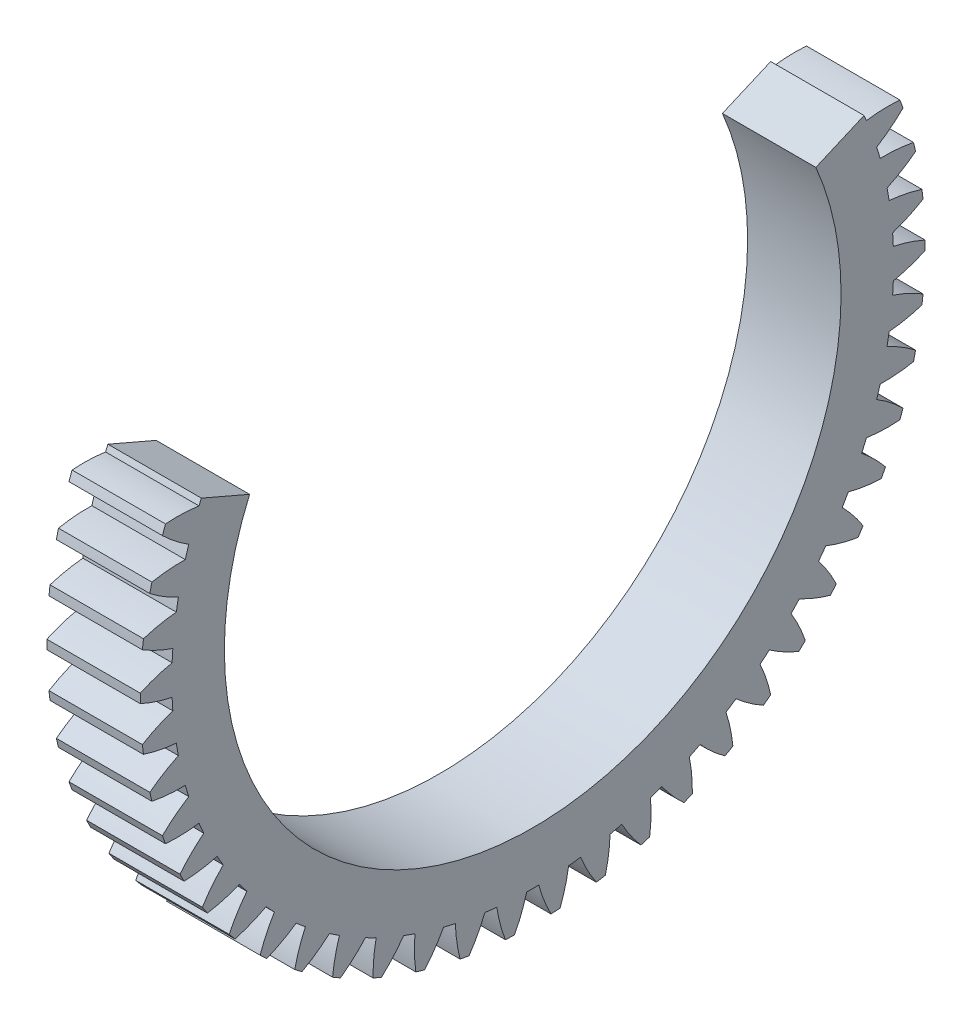
SolidWorks part; units mm, degrees
ref_plane "Plane1" through (0, 0, 0) normal (0, 0, 1) x (1, 0, 0)
ref_plane "Plane2" through (0, 0, 0) normal (0, 1, 0) x (1, 0, 0)
ref_plane "Plane3" through (0, 0, 0) normal (1, 0, 0) x (0, 0, -1)
other "Configuration Table"
sketch "HoldingSke" plane through (0, 0, 0) normal (0, 1, 0) x (1, 0, 0)
  line L0 (0, 0) -> (0.3919, -0.5393)
  line L1 (-15, 0) -> (100, 0) construction
  line L2 (0, 0) -> (-2.1039, 2.3779)
  line L3 (0, 0) -> (-11.863, 4.5341)
  line L4 (0, 0) -> (5.0761, 6.9867)
  line L5 (0, 0) -> (-46.8476, -17.4728)
  line L6 (0, 0) -> (-4.9738, -3.3558)
  line L7 (-2.1039, 2.3779) -> (8.6586, 51.2059)
  line L8 (-76.2, 54.61) -> (-72.9, 54.61)
  line L9 (-71.009, 38.7566) -> (-53.1078, 45.2721)
  line L10 (-76.2, 71.12) -> (104.1128, 71.12)
  line L11 (0, 0) -> (-6, 0)
  line L12 (-76.2, 101.6) -> (-76.147, 101.6)
  line L13 (24.9733, 27.94) -> (52.9518, 28.4284)
  line L14 (24.9733, 27.94) -> (24.9743, 27.94)
  line L15 (24.9733, 27.94) -> (100.4006, 29.5858)
  line L16 (-63.627, -1.5) -> (-12.827, -1.5)
  circle A0 centre (0, 0) radius 21
  circle A1 centre (0, 0) radius 37.5
  circle A2 centre (0, 0) radius 37.5
  circle A3 centre (0, 0) radius 21
  dimension "MHD" = 75
  dimension "Hub_dia" = 75
  dimension "Bore" = 42
  dimension "MBD" = 42
  dimension "Num_teeth" = 54
  dimension "Pitch" = 0.6667
  dimension "Overall_len" = 50
  dimension "Show_teeth" = 54
  dimension "Thickness" = 6
  dimension "OAL" = 50.0001
  dimension "T_dim" = 3.3
  dimension "Ap" = 20
  dimension "H" = 19.05
  dimension "Pitch_radius" = 180.3128
  dimension "Width" = 6
  dimension "Backlash" = 0.053
  dimension "Addendum_fac" = 1
  dimension "Dedendum_fac" = 1.25
  dimension "Clearance_fac" = 0.25
  dimension "Dedendum_add" = 0.001
  dimension "Module" = 1.5
sketch "BasProSke" plane through (0, 0, 0) normal (0, 1, 0) x (1, 0, 0)
  line L0 (-10, 0) -> (60, 0) construction
  line L1 (0, 0) -> (0, 42)
  line L2 (0, 0) -> (10, 0)
  line L3 (10, 0) -> (10, 42)
  line L4 (10, 42) -> (0, 42)
  dimension "Thickness" = 10
  dimension "Diameter" = 84
revolve "Base-Revolve" add sketch "BasProSke" angle 360 about L0
sketch "TooCutSke" plane through (0, 0, 0) normal (1, 0, 0) x (0, 0, -1)
  line L1 (0, 0) -> (0, 107) construction
  line L2 (0, 0) -> (-1.2707, 40.4801) construction
  line L3 (0, 0) -> (-4.708, 80.8339) construction
  line L4 (-1.2707, 40.4801) -> (-2.354, 40.417) construction
  arc A0 (0.645, 38.6186) -> (-0.645, 38.6186) centre (0, 0) ccw
  arc A1 (1.9691, 41.9792) -> (-1.9691, 41.9792) centre (0, 0) ccw
  circle A2 centre (0, 0) radius 40.5 construction
  circle A3 centre (0, 0) radius 38.0576 construction
  arc A4 (-0.645, 38.6186) -> (-1.9691, 41.9792) centre (-16.2853, 34.3972) ccw
  arc A5 (1.9691, 41.9792) -> (0.645, 38.6186) centre (16.2853, 34.3972) ccw
  dimension "Root_dia" = 77.248
  dimension "Overcut_dia" = 84.0508
  dimension "Pitch_dia" = 81
  dimension "Base_dia" = 76.1151
  dimension "Flank_rad" = 16.2
  dimension "Half_ang" = 3.333
  dimension "Half_CT" = 1.0852
extrude "ToothCut" cut sketch "TooCutSke" along normal through all
fillet "Breaks" [suppressed] radius 0.03
fillet "RootFillets" [suppressed] radius 0.376
pattern_circular "TeethCuts" count 54 every 6.667 about axis through (-10, 0, 0) along (1, 0, 0) of "ToothCut", "RootFillets", "Breaks"
sketch "HubNeaOneSke" plane through (0, 0, 0) normal (-1, 0, 0) x (0, 0, 1)
  circle A0 centre (0, 0) radius 37.5
  dimension "Diameter" = 75
extrude "HubNearOne" [suppressed] add sketch "HubNeaOneSke" along normal blind 40.0001
sketch "HubNeaBotSke" plane through (0, 0, 0) normal (-1, 0, 0) x (0, 0, 1)
  circle A0 centre (0, 0) radius 37.5
  dimension "Diameter" = 75
extrude "HubNearBoth" [suppressed] add sketch "HubNeaBotSke" along normal blind 20
ref_plane "FarPln" through (10, 0, 0) normal (1, 0, 0) x (0, 0, -1)
sketch "HubFarSke" plane through (10, 0, 0) normal (1, 0, 0) x (0, 0, -1)
  circle A0 centre (0, 0) radius 37.5
  dimension "Diameter" = 75
extrude "HubFar" [suppressed] add sketch "HubFarSke" along normal blind 20
sketch "BorSke" plane through (0, 0, 0) normal (1, 0, 0) x (0, 0, -1)
  circle A0 centre (0, 0) radius 33
  dimension "Diameter" = 66
extrude "Bore" cut sketch "BorSke" along normal mid plane 100.0001
sketch "KeySke" plane through (0, 0, 0) normal (1, 0, 0) x (0, 0, -1)
  line L0 (-6, 0) -> (-6, 24.3)
  line L1 (-6, 24.3) -> (6, 24.3)
  line L2 (6, 24.3) -> (6, 0)
  line L3 (0, 0) -> (0, 34) construction
  line L4 (-6, 0) -> (6, 0)
  dimension "Offset" = 24.3
  dimension "Width" = 12
extrude "Keyway" [suppressed] cut sketch "KeySke" along normal mid plane 100.0001
pattern_circular "Keyway2" [suppressed] count 2 every 90 about axis through (-10, 0, 0) along (1, 0, 0)
sketch "Sketch1" plane through (0, 0, 0) normal (-1, 0, 0) x (0, 0, 1)
  line L0 (0, 0) -> (0, 43) construction
  line L1 (30.3011, 13.0706) -> (39.4833, 17.0314)
  line L2 (-30.3011, 13.0706) -> (-39.4833, 17.0314)
  line L3 (-30.3011, 13.0706) -> (0, 0) construction
  line L4 (0, 0) -> (30.3011, 13.0706) construction
  arc A0 (-39.4833, 17.0314) -> (39.4833, 17.0314) centre (0, 0) cw
  arc A1 (-30.3011, 13.0706) -> (30.3011, 13.0706) centre (0, 0) cw
  circle A2 centre (0, 0) radius 33 construction
  arc A4 (35.7157, 14.7038) -> (35.2048, 15.8883) centre (0, 0) ccw construction
  arc A5 (-35.2048, 15.8883) -> (-35.7157, 14.7038) centre (0, 0) ccw construction
  point P9 (0, 0)
  point P13 (35.4652, 15.2982)
  point P17 (-35.4652, 15.2982)
  dimension "D1" = 43
extrude "Cut-Extrude1" cut sketch "Sketch1" against normal through all
equation "' \"Module@HoldingSke\" = 6.35"
equation "' \"Num_teeth@HoldingSke\" = 12"
equation "' \"Ap@HoldingSke\" =  20"
equation "' \"Ap@HoldingSke\" = 20"
equation "' \"Width@HoldingSke\" = 0.5 * 25.4"
equation "' \"Hub_dia@HoldingSke\"= 1 * 25.4"
equation "' \"Hub_dia@HoldingSke\" = 1 * 25.4"
equation "' \"Overall_len@HoldingSke\" = 1.0 * 25.4"
equation "' \"Bore@HoldingSke\" = 0.75 * 25.4"
equation "' \"T_dim@HoldingSke\" = 0.1 * 25.4"
equation "' \"Width@KeySke\" = 0.25 * 25.4"
equation "' \"Show_teeth@HoldingSke\" = 13"
equation "' \"Backlash@HoldingSke\" = 0.009 * 25.4"
equation "' \"Addendum_fac@HoldingSke\" = 1.0"
equation "' \"Dedendum_fac@HoldingSke\" = 1.25"
equation "' \"Dedendum_add@HoldingSke\" = 0.00005 * 25.4"
equation "' \"Clearance_fac@HoldingSke\" = 0.25"
equation "\"Pitch@HoldingSke\" = 1 / \"Module@HoldingSke\""
equation "\"Overcut_dia@TooCutSke\" = (\"Num_teeth@HoldingSke\" + 2 * \"Addendum_fac@HoldingSke\") / \"Pitch@HoldingSke\" + 0.002 * 25.4"
equation "\"Pitch_dia@TooCutSke\" = \"Num_teeth@HoldingSke\" / \"Pitch@HoldingSke\""
equation "\"Base_dia@TooCutSke\" = \"Num_teeth@HoldingSke\" / \"Pitch@HoldingSke\" * cos((\"Ap@HoldingSke\"  * 3.14159265 / 180))"
equation "\"Root_dia@TooCutSke\" = (\"Num_teeth@HoldingSke\" + 2) / \"Pitch@HoldingSke\" - 2 * (\"Addendum_fac@HoldingSke\" + \"Dedendum_fac@HoldingSke\") / \"Pitch@HoldingSke\" - \"Dedendum_add@HoldingSke\" * 2"
equation "\"Half_ang@TooCutSke\" = 180 / \"Num_teeth@HoldingSke\""
equation "\"Half_CT@TooCutSke\" = \"Num_teeth@HoldingSke\" / \"Pitch@HoldingSke\" * sin((3.14159265 / 2 / \"Num_teeth@HoldingSke\")) / 2 - 7 * \"Backlash@HoldingSke\" / 4"
equation "\"Flank_rad@TooCutSke\" = \"Num_teeth@HoldingSke\" / \"Pitch@HoldingSke\" / 5"
equation "\"Radius@RootFillets\" = \"Clearance_fac@HoldingSke\" / \"Pitch@HoldingSke\" + \"Dedendum_add@HoldingSke\""
equation "\"Break_rad@Breaks\" = 0.02 / \"Pitch@HoldingSke\""
equation "\"Thickness@HoldingSke\" = \"Width@HoldingSke\""
equation "\"OAL@HoldingSke\" = \"Thickness@HoldingSke\""
equation "\"MHD@HoldingSke\" = (\"Num_teeth@HoldingSke\" + 2) / \"Pitch@HoldingSke\" - 2 * (\"Addendum_fac@HoldingSke\" + \"Dedendum_fac@HoldingSke\")  / \"Pitch@HoldingSke\" - \"Dedendum_add@HoldingSke\" * 2"
equation "\"MBD@HoldingSke\" = (\"Num_teeth@HoldingSke\" + 2) / \"Pitch@HoldingSke\" - 2 * (\"Addendum_fac@HoldingSke\" + \"Dedendum_fac@HoldingSke\")  / \"Pitch@HoldingSke\" - \"Dedendum_add@HoldingSke\" * 2 - 0.002 * 25.4"
equation "\"MHD@HoldingSke\" = ((sgn( \"MHD@HoldingSke\" - \"Hub_dia@HoldingSke\" )-1)*( \"MHD@HoldingSke\" - \"Hub_dia@HoldingSke\" ))/-2+ \"Hub_dia@HoldingSke\""
equation "\"MBD@HoldingSke\" = ((sgn( \"MBD@HoldingSke\" - \"Bore@HoldingSke\" )-1)*( \"MBD@HoldingSke\" - \"Bore@HoldingSke\" ))/-2+ \"Bore@HoldingSke\""
equation "\"OAL@HoldingSke\" = ((sgn( \"OAL@HoldingSke\" - \"Overall_len@HoldingSke\" )+1)*( \"OAL@HoldingSke\" - \"Overall_len@HoldingSke\" ))/2 + \"Overall_len@HoldingSke\" + 0.000002 * 25.4"
equation "\"Num_teeth@TeethCuts\" = int( \"Show_teeth@HoldingSke\" ) + 1"
equation "\"Num_teeth@TeethCuts\" = ((sgn( \"Num_teeth@TeethCuts\" - \"Num_teeth@HoldingSke\" )-1)*( \"Num_teeth@TeethCuts\" - \"Num_teeth@HoldingSke\" ))/-2+ \"Num_teeth@HoldingSke\""
equation "\"Num_teeth@TeethCuts\" = ((sgn( \"Num_teeth@TeethCuts\" - 2.0)+1)*( \"Num_teeth@TeethCuts\" - 2.0))/2 +2.0"
equation "\"Angle@TeethCuts\" = 360.0 / \"Num_teeth@HoldingSke\""
equation "\"Diameter@BasProSke\" = (\"Num_teeth@HoldingSke\" + 2 * \"Addendum_fac@HoldingSke\") / \"Pitch@HoldingSke\""
equation "' \"Fillet_rad@BasProSke\" =  \"Thickness@HoldingSke\" * 0.05"
equation "' \"Fillet_rad@BasProSke\" = \"Thickness@HoldingSke\" * 0.05"
equation "\"MHD@HoldingSke\" = ((sgn( \"MHD@HoldingSke\" - \"Root_dia@TooCutSke\" )-1)*( \"MHD@HoldingSke\" - \"Root_dia@TooCutSke\" ))/-2+ \"Root_dia@TooCutSke\""
equation "\"Diameter@HubNeaOneSke\" = \"MHD@HoldingSke\""
equation "\"Length@HubNearOne\" = \"OAL@HoldingSke\" - \"Thickness@BasProSke\""
equation "\"Diameter@HubNeaBotSke\" = \"MHD@HoldingSke\""
equation "\"Length@HubNearBoth\" = ( \"OAL@HoldingSke\" - \"Thickness@BasProSke\" ) / 2.0"
equation "\"Thickness@FarPln\" = \"Thickness@BasProSke\""
equation "\"Diameter@HubFarSke\" = \"MHD@HoldingSke\""
equation "\"Length@HubFar\" = ( \"OAL@HoldingSke\" - \"Thickness@BasProSke\" ) / 2.0"
equation "\"D1@Bore\" = \"OAL@HoldingSke\" * 2.0"
equation "\"D1@Keyway\" = \"OAL@HoldingSke\" * 2.0"
equation "\"Offset@KeySke\" = \"T_dim@HoldingSke\" + \"MBD@HoldingSke\" / 2.0"
